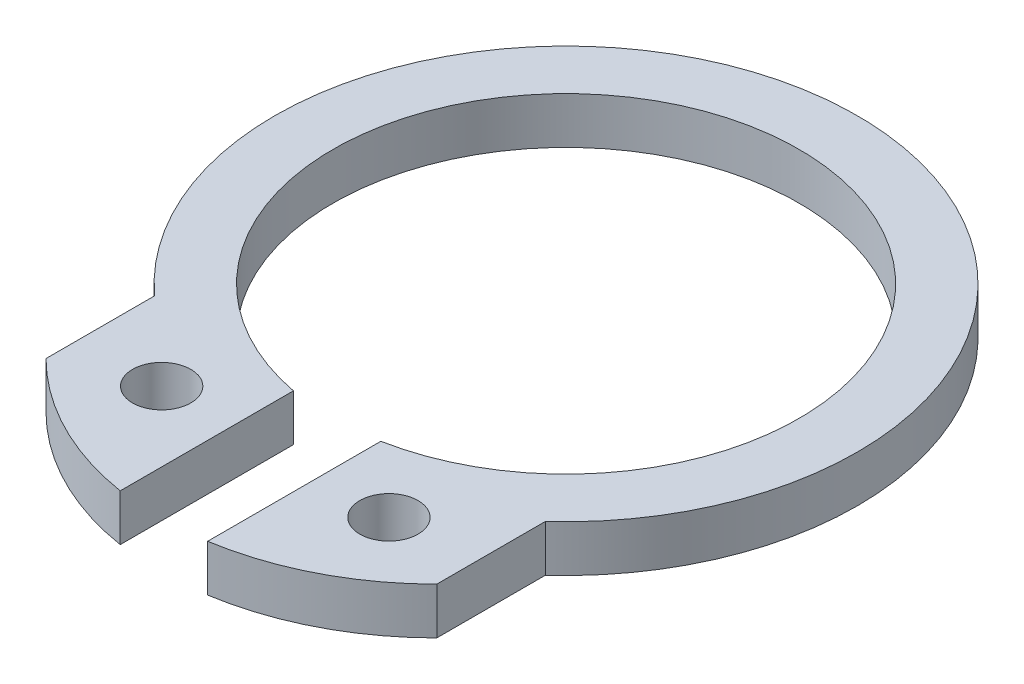
SolidWorks part; units mm, degrees
ref_plane "Alzado" through (0, 0, 0) normal (0, 0, 1) x (1, 0, 0)
ref_plane "Planta" through (0, 0, 0) normal (0, 1, 0) x (1, 0, 0)
ref_plane "Vista lateral" through (0, 0, 0) normal (1, 0, 0) x (0, 0, -1)
sketch "Croquis1" plane through (0, 0, 0) normal (0, 1, 0) x (1, 0, 0)
  line L0 (0, 0) -> (0, -9.2728) construction
  line L1 (-0.75, -2.1805) -> (0, -2.1805)
  line L2 (-3.3534, -3.7087) -> (-3.3534, -5.5725)
  line L3 (3.3534, -3.7087) -> (3.3534, -5.5725)
  line L4 (-0.75, -5.5725) -> (0.75, -5.5725) construction
  line L5 (-0.75, -6.9018) -> (-0.75, -3.9291)
  line L6 (0.75, -6.9018) -> (0.75, -3.9291)
  line L7 (-0.75, -4.9906) -> (0.75, -4.9906) construction
  line L8 (-3.3534, -4.9906) -> (3.3534, -4.9906) construction
  line L9 (1.95, -4.9906) -> (-1.95, -4.9906)
  arc A0 (0.75, -3.9291) -> (-0.75, -3.9291) centre (0, 0) ccw
  arc A1 (3.3534, -3.7087) -> (-3.3534, -3.7087) centre (0, 0) ccw
  arc A2 (-3.3534, -5.5725) -> (-0.75, -6.9018) centre (0, -2.2191) ccw
  arc A3 (0.75, -6.9018) -> (3.3534, -5.5725) centre (0, -2.2191) ccw
  circle A4 centre (-1.95, -4.9906) radius 0.5
  circle A5 centre (1.95, -4.9906) radius 0.5
  point P8 (0, -2.1805)
  point P14 (0, -5.5725)
  point P27 (0, -4.9906)
  dimension "D1" = 10
  dimension "D2" = 8
  dimension "D5" = 1
  dimension "D3" = 1.5
  dimension "D4" = 3.9
extrude "Saliente-Extruir1" add sketch "Croquis1" along normal blind 0.8
